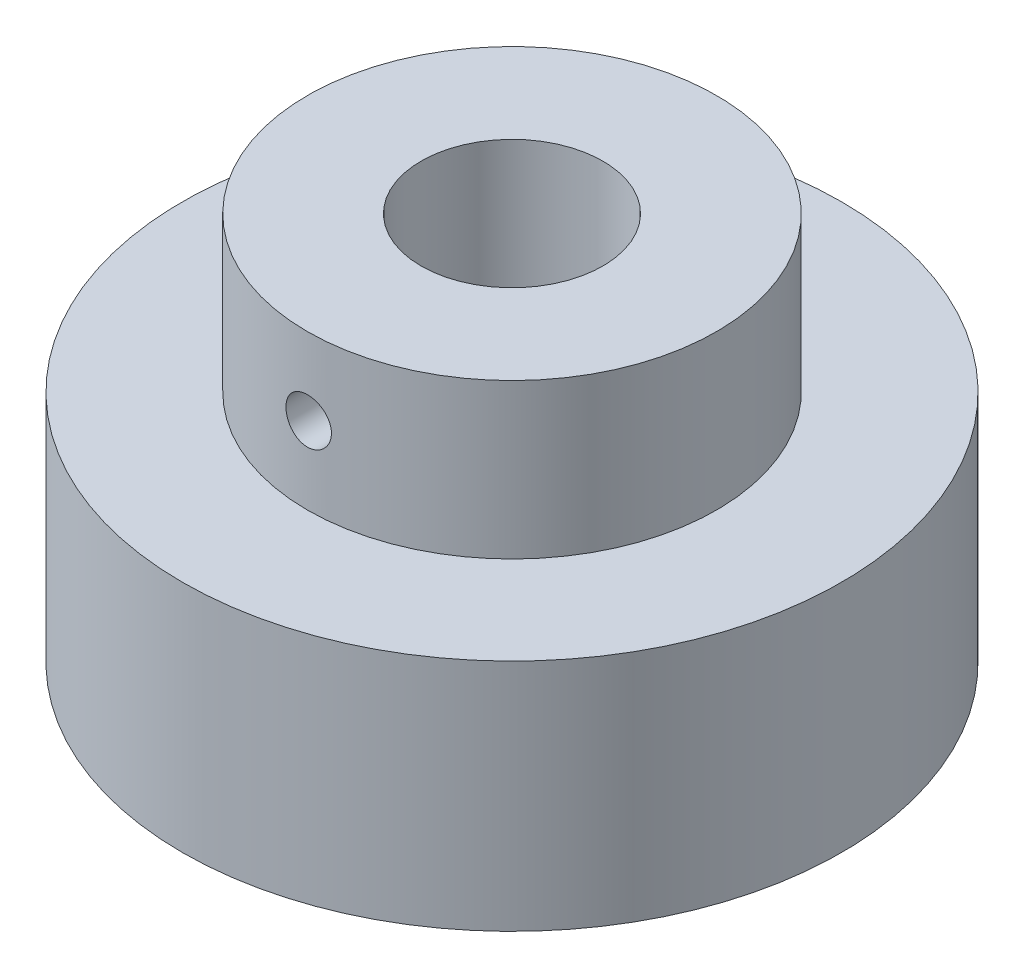
SolidWorks part; units mm, degrees
ref_plane "前基準面" through (0, 0, 0) normal (0, 0, 1) x (1, 0, 0)
ref_plane "上基準面" through (0, 0, 0) normal (0, 1, 0) x (1, 0, 0)
ref_plane "右基準面" through (0, 0, 0) normal (1, 0, 0) x (0, 0, -1)
sketch "草圖1" plane through (0, 0, 0) normal (0, 1, 0) x (1, 0, 0)
  circle A0 centre (0, 0) radius 14.5
  circle A1 centre (0, 0) radius 4
  dimension "D1" = 29
  dimension "D2" = 8
extrude "填料-伸長1" add sketch "草圖1" along normal blind 10.3
sketch "草圖2" plane through (0, 10.3, 0) normal (0, 1, 0) x (1, 0, 0)
  circle A0 centre (0, 0) radius 4 construction
  circle A1 centre (0, 0) radius 4
  circle A2 centre (0, 0) radius 9
  dimension "D1" = 18
extrude "填料-伸長2" add sketch "草圖2" along normal blind 6.8
sketch "草圖3" plane through (0, 0, 0) normal (0, 0, 1) x (1, 0, 0)
  line L0 (0, 18.1992) -> (0, -1.4413) construction
  line L1 (9, 17.1) -> (-9, 17.1) construction
  circle A0 centre (0, 13.7) radius 1
  dimension "D1" = 2
  dimension "D2" = 3.4
extrude "除料-伸長1" cut sketch "草圖3" along normal up to next
